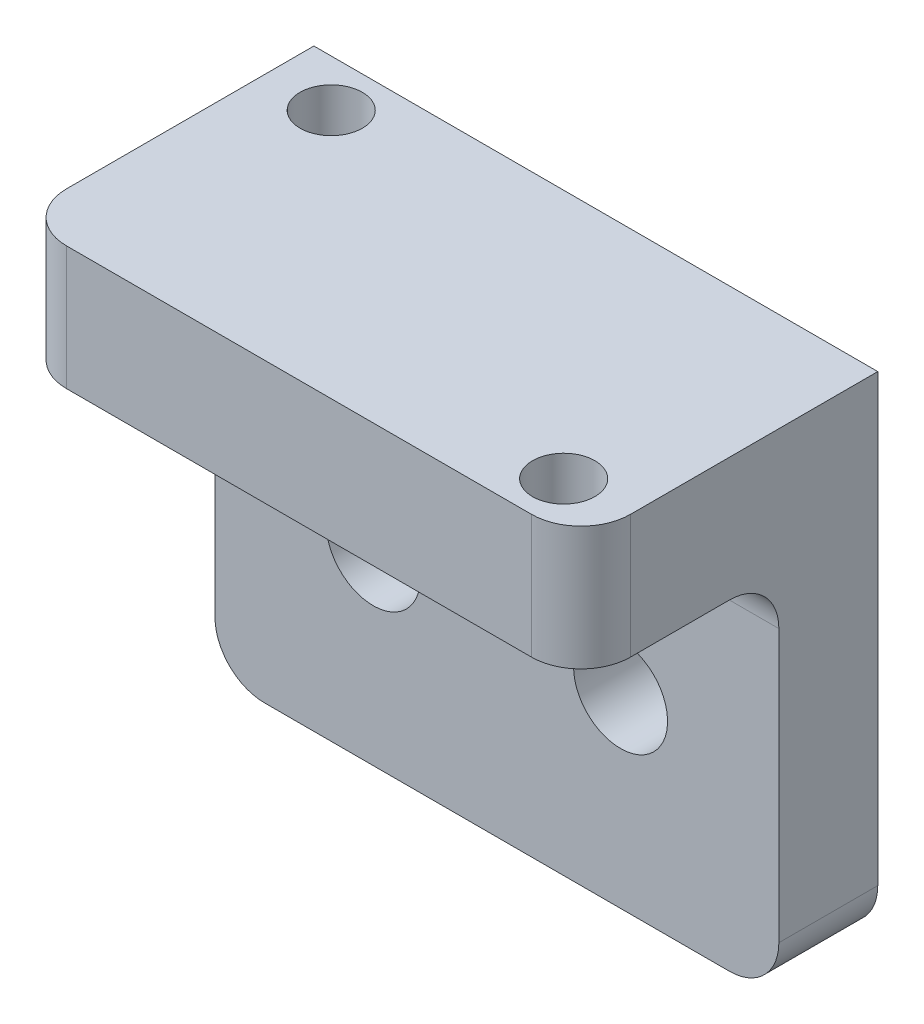
SolidWorks part; units mm, degrees
ref_plane "Front Plane" through (0, 0, 0) normal (0, 0, 1) x (1, 0, 0)
ref_plane "Top Plane" through (0, 0, 0) normal (0, 1, 0) x (1, 0, 0)
ref_plane "Right Plane" through (0, 0, 0) normal (1, 0, 0) x (0, 0, -1)
sketch "Sketch1" plane through (0, 0, 0) normal (0, 1, 0) x (1, 0, 0)
  line L1 (-11.176, -5.207) -> (11.176, -5.207) construction
  line L2 (-11.176, -5.207) -> (-11.176, 5.207) construction
  line L3 (-11.176, 5.207) -> (11.176, 5.207) construction
  line L4 (11.176, -5.207) -> (11.176, 5.207) construction
  line L5 (0, 5.207) -> (0, -5.207) construction
  line L6 (-11.176, 0) -> (11.176, 0) construction
  line L7 (-14.478, -7.62) -> (14.478, -7.62)
  line L8 (-14.478, -7.62) -> (-14.478, 7.62)
  line L9 (-14.478, 7.62) -> (14.478, 7.62)
  line L10 (14.478, -7.62) -> (14.478, 7.62)
  line L11 (0, 7.62) -> (0, -7.62) construction
  line L12 (-14.478, 0) -> (14.478, 0) construction
  circle A0 centre (-11.176, 5.207) radius 1.6002
  circle A1 centre (11.176, -5.207) radius 1.6002
  point P0 (0, 0)
  point P6 (0, 0)
  dimension "D1" = 22.352
  dimension "D3" = 3.2004
  dimension "D4" = 15.24
  dimension "D2" = 10.414
  dimension "D5" = 28.956
extrude "Boss-Extrude1" add sketch "Sketch1" against normal blind 6.35
sketch "Sketch2" plane through (0, 0, -7.62) normal (0, 0, -1) x (-1, 0, 0)
  line L0 (14.478, -6.35) -> (14.478, 0) construction
  line L1 (-14.478, -6.35) -> (14.478, -6.35)
  line L2 (-14.478, -6.35) -> (-14.478, -25.4)
  line L3 (-14.478, -25.4) -> (14.478, -25.4)
  line L4 (14.478, -6.35) -> (14.478, -25.4)
  line L5 (0, -25.4) -> (0, -6.35) construction
  line L6 (-14.478, -15.875) -> (14.478, -15.875) construction
  circle A0 centre (-6.35, -15.875) radius 2.413
  circle A1 centre (6.35, -15.875) radius 2.413
  point P116 (0, -15.875)
  dimension "D2" = 4.826
  dimension "D3" = 12.7
  dimension "D1" = 19.05
extrude "Boss-Extrude2" add sketch "Sketch2" against normal blind 5.08
fillet "Fillet1" radius 2.54 5 edges at (14.478, -25.4, -5.08) (-14.478, -25.4, -5.08) (14.478, -3.175, 7.62) (-14.478, -3.175, 7.62) (0, -6.35, -2.54)
